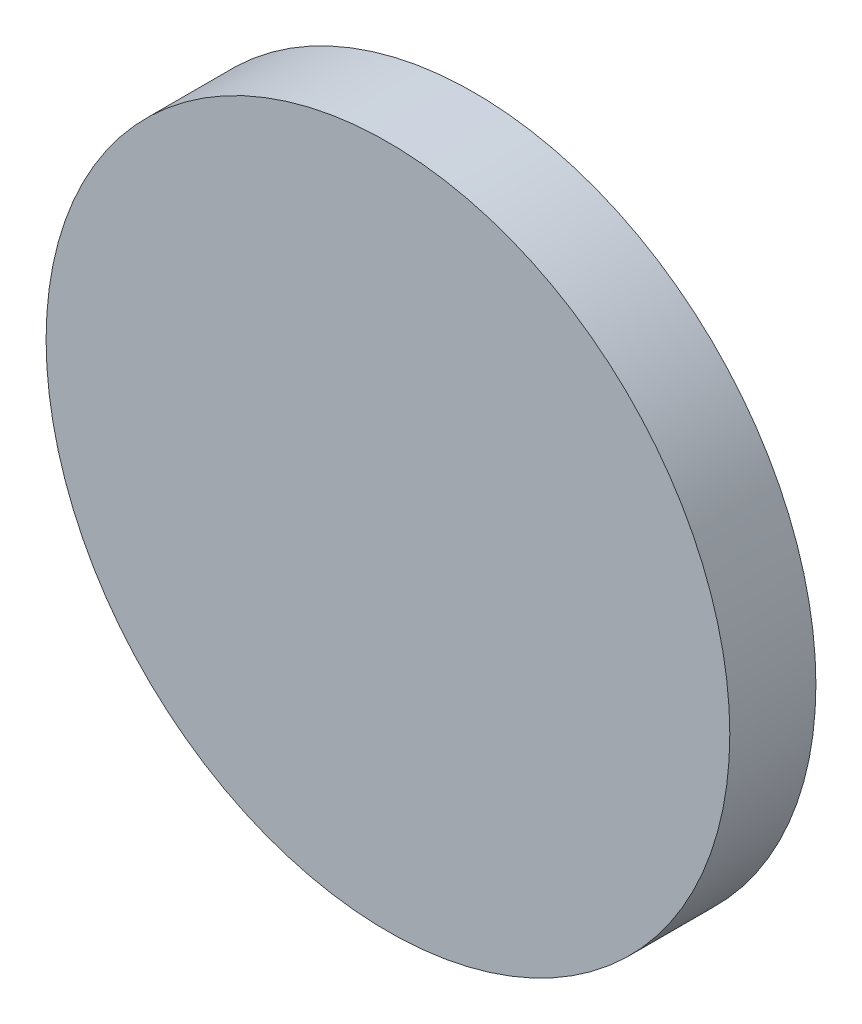
SolidWorks part; units mm, degrees
ref_plane "Front Plane" through (0, 0, 0) normal (0, 0, 1) x (1, 0, 0)
ref_plane "Top Plane" through (0, 0, 0) normal (0, 1, 0) x (1, 0, 0)
ref_plane "Right Plane" through (0, 0, 0) normal (1, 0, 0) x (0, 0, -1)
sketch "Sketch1" plane through (0, 0, 0) normal (0, 0, 1) x (1, 0, 0)
  circle A0 centre (0, 0) radius 13.5
  dimension "D1" = 27
extrude "Boss-Extrude1" add sketch "Sketch1" along normal blind 3.4
sketch "Sketch2" plane through (0, 0, 0) normal (0, 0, -1) x (-1, 0, 0)
  circle A0 centre (0, 0) radius 13
  dimension "D1" = 26
extrude "Cut-Extrude1" cut sketch "Sketch2" against normal offset from surface (2.4 mm away) 1 up to face at (13.5, 0, 3.4)
